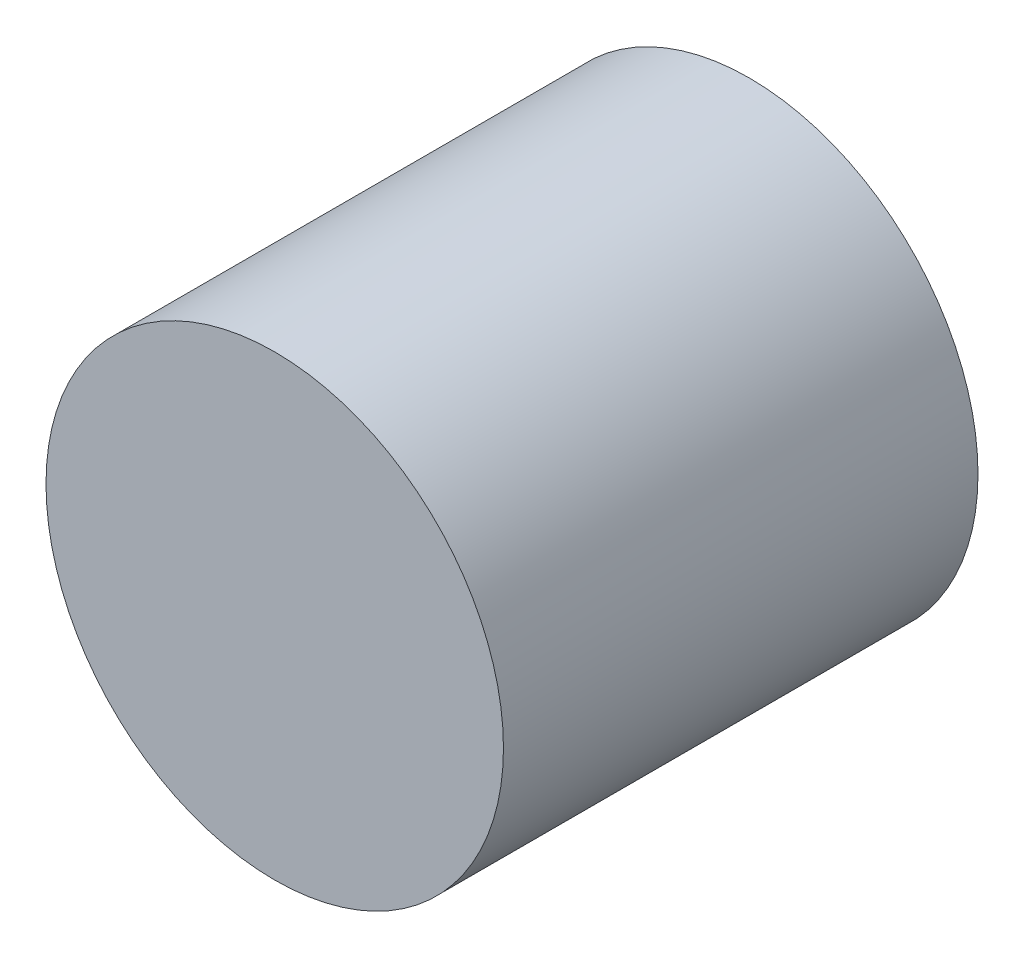
SolidWorks part; units mm, degrees
ref_plane "Front Plane" through (0, 0, 0) normal (0, 0, 1) x (1, 0, 0)
ref_plane "Top Plane" through (0, 0, 0) normal (0, 1, 0) x (1, 0, 0)
ref_plane "Right Plane" through (0, 0, 0) normal (1, 0, 0) x (0, 0, -1)
sketch "Sketch1" plane through (0, 0, 0) normal (0, 0, 1) x (1, 0, 0)
  circle A0 centre (0, 0) radius 24.4859
extrude "Boss-Extrude1" add sketch "Sketch1" along normal blind 50.8
sketch "Sketch3" plane through (0, 0, 0) normal (0, 0, -1) x (-1, 0, 0)
  circle A0 centre (24.4706, 0.8668) radius 2.4234
  circle A1 centre (0, 0) radius 24.4859 construction
